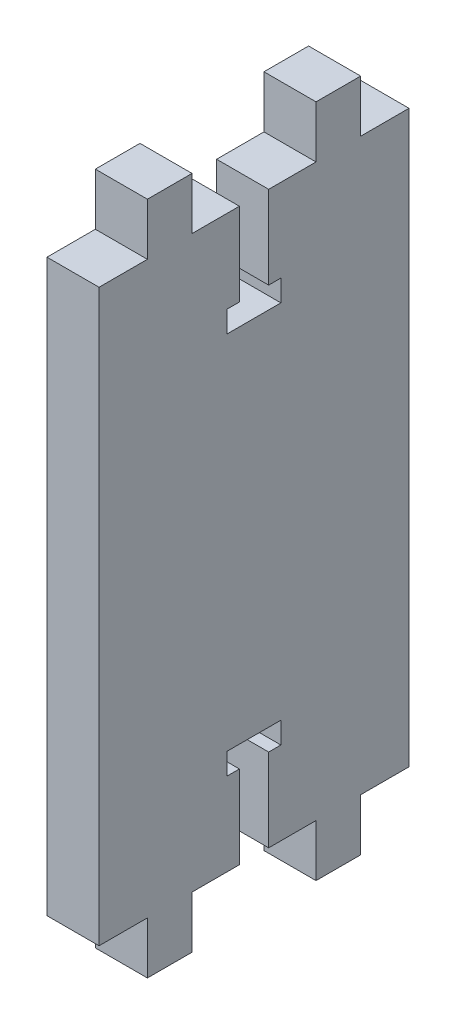
SolidWorks part; units mm, degrees
material "Oak"
ref_plane "Front Plane" through (0, 0, 0) normal (0, 0, 1) x (1, 0, 0)
ref_plane "Top Plane" through (0, 0, 0) normal (0, 1, 0) x (1, 0, 0)
ref_plane "Right Plane" through (0, 0, 0) normal (1, 0, 0) x (0, 0, -1)
sketch "Sketch1" plane through (0, 0, 0) normal (1, 0, 0) x (0, 0, -1)
  line L0 (-15.875, 0) -> (15.875, 0) construction
  line L1 (-15.875, -29.21) -> (-1.5, -29.21)
  line L2 (-15.875, -29.21) -> (-15.875, 29.21)
  line L3 (-15.875, 29.21) -> (-10.922, 29.21)
  line L4 (15.875, -29.21) -> (15.875, 29.21)
  line L5 (-15.875, -29.21) -> (15.875, 29.21) construction
  line L6 (-15.875, 29.21) -> (15.875, -29.21) construction
  line L7 (-10.922, -29.21) -> (-6.35, -29.21)
  line L8 (-10.922, -29.21) -> (-10.922, -34.544)
  line L9 (-10.922, -34.544) -> (-6.35, -34.544)
  line L10 (-6.35, -29.21) -> (-6.35, -34.544)
  line L11 (6.35, -29.21) -> (10.922, -29.21)
  line L12 (6.35, -29.21) -> (6.35, -34.544)
  line L13 (6.35, -34.544) -> (10.922, -34.544)
  line L14 (10.922, -29.21) -> (10.922, -34.544)
  line L15 (0, 0) -> (0, -31.75) construction
  line L16 (6.35, 34.544) -> (10.922, 34.544)
  line L17 (10.922, 29.21) -> (10.922, 34.544)
  line L19 (6.35, 29.21) -> (6.35, 34.544)
  line L20 (-6.35, 29.21) -> (-6.35, 34.544)
  line L21 (-10.922, 34.544) -> (-6.35, 34.544)
  line L22 (-10.922, 29.21) -> (-10.922, 34.544)
  line L23 (1.5, 20.71) -> (2.75, 20.71)
  line L25 (-1.5, 29.21) -> (-1.5, 20.71)
  line L26 (-1.5, 18.51) -> (1.5, 18.51)
  line L27 (1.5, 29.21) -> (1.5, 20.71)
  line L28 (1.5, 29.21) -> (6.35, 29.21)
  line L29 (-6.35, 29.21) -> (-1.5, 29.21)
  line L30 (-2.75, 20.71) -> (-1.5, 20.71)
  line L31 (-2.75, 20.71) -> (-2.75, 18.51)
  line L32 (-2.75, 18.51) -> (2.75, 18.51)
  line L33 (2.75, 20.71) -> (2.75, 18.51)
  line L34 (10.922, 29.21) -> (15.875, 29.21)
  line L35 (2.75, -20.71) -> (2.75, -18.51)
  line L36 (1.5, -20.71) -> (2.75, -20.71)
  line L37 (-2.75, -20.71) -> (-1.5, -20.71)
  line L38 (-2.75, -20.71) -> (-2.75, -18.51)
  line L39 (-2.75, -18.51) -> (2.75, -18.51)
  line L40 (-1.5, -18.51) -> (1.5, -18.51)
  line L41 (1.5, -29.21) -> (1.5, -20.71)
  line L42 (-1.5, -29.21) -> (-1.5, -20.71)
  line L43 (1.5, -29.21) -> (15.875, -29.21)
  point P0 (0, 0)
  point P16 (6.35, -31.877)
  point P27 (0, 31.75)
  point P29 (0, 22.15)
  dimension "D1" = 58.42
  dimension "D2" = 31.75
  dimension "D3" = 4.572
  dimension "D4" = 4.572
  dimension "D5" = 5.334
  dimension "D6" = 5.334
  dimension "D7" = 12.7
  dimension "D8" = 6.35
  dimension "D9" = 3
  dimension "D10" = 10.7
  dimension "D11" = 5.5
  dimension "D12" = 0
  dimension "D13" = 2.2
  dimension "D14" = 0
extrude "Boss-Extrude1" add sketch "Sketch1" along normal blind 5.334 contours L41 L43 L11 L4 L34 L17 L16 L19 L28 L27 L23 L33 L32 L26 L31 L30 L25 L29 L20 L21 L22 L3 L2 L1 L42 L37 L38 L39 L35 L36 | L8 L7 L10 L9
